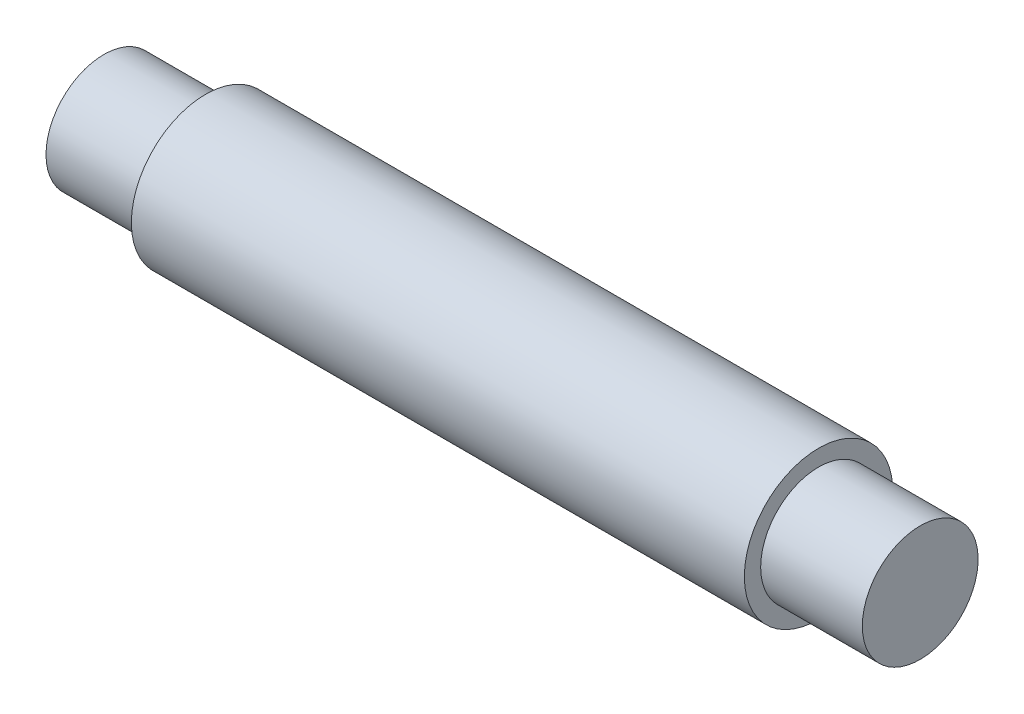
SolidWorks part; units mm, degrees
ref_plane "Front Plane" through (0, 0, 0) normal (0, 0, 1) x (1, 0, 0)
ref_plane "Top Plane" through (0, 0, 0) normal (0, 1, 0) x (1, 0, 0)
ref_plane "Right Plane" through (0, 0, 0) normal (1, 0, 0) x (0, 0, -1)
sketch "Sketch1" plane through (0, 0, 0) normal (0, 0, 1) x (1, 0, 0)
  line L0 (-27.5, 0) -> (27.5, 0) construction
  line L2 (0, 5) -> (0, 0) construction
  line L3 (-20.65, 5) -> (20.65, 5)
  line L4 (-20.65, 5) -> (-20.65, 0)
  line L5 (-27.5, 0) -> (27.5, 0)
  line L6 (20.65, 5) -> (20.65, 0)
  line L9 (-20.65, 3.9) -> (-27.5, 3.9)
  line L10 (-20.65, 3.9) -> (-20.65, 0)
  line L12 (-27.5, 3.9) -> (-27.5, 0)
  line L13 (20.65, 3.9) -> (27.5, 3.9)
  line L14 (20.65, 3.9) -> (20.65, 0)
  line L16 (27.5, 3.9) -> (27.5, 0)
  dimension "D1" = 41.3
  dimension "D3" = 55
revolve "Revolve1" add sketch "Sketch1" angle 360 about L5
